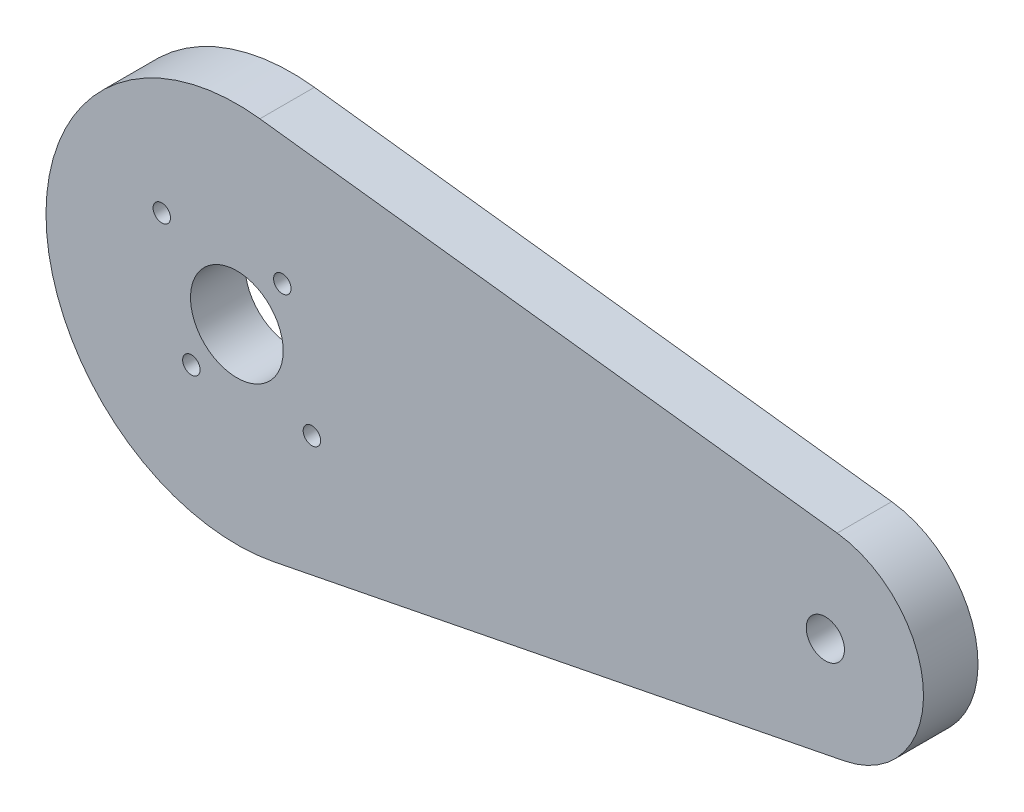
SolidWorks part; units mm, degrees
ref_plane "Front Plane" through (0, 0, 0) normal (0, 0, 1) x (1, 0, 0)
ref_plane "Top Plane" through (0, 0, 0) normal (0, 1, 0) x (1, 0, 0)
ref_plane "Right Plane" through (0, 0, 0) normal (1, 0, 0) x (0, 0, -1)
sketch "Sketch1" plane through (0, 0, 0) normal (0, 0, 1) x (1, 0, 0)
  line L0 (-14.9674, 57.7752) -> (33.7427, 59.5858) construction
  line L1 (-20.22, 57.58) -> (33.7427, 59.5858) construction
  line L2 (34.8283, 68.5201) -> (-18.1092, 74.9522)
  line L3 (-16.8253, 40.4124) -> (35.4886, 50.7568)
  circle A0 centre (-20.22, 57.58) radius 17.5 construction
  circle A1 centre (-20.22, 57.58) radius 17.5 construction
  circle A2 centre (33.7427, 59.5858) radius 9 construction
  arc A3 (-18.1092, 74.9522) -> (-16.8253, 40.4124) centre (-20.22, 57.58) ccw
  arc A4 (34.8283, 68.5201) -> (35.4886, 50.7568) centre (33.7427, 59.5858) cw
  circle A5 centre (33.7427, 59.5858) radius 1.75
  circle A6 centre (-20.22, 57.58) radius 4.25
  circle A7 centre (-27.1013, 62.9846) radius 0.8
  circle A8 centre (-16.0507, 62.8884) radius 0.8
  circle A9 centre (-13.3387, 52.1754) radius 0.8
  circle A10 centre (-24.3893, 52.2716) radius 0.8
  dimension "D1" = 18
  dimension "D2" = 3.5
  dimension "D3" = 8.5
  dimension "D6" = 52.9375
  dimension "D9" = 53.3268
extrude "Boss-Extrude1" add sketch "Sketch1" against normal blind 5
